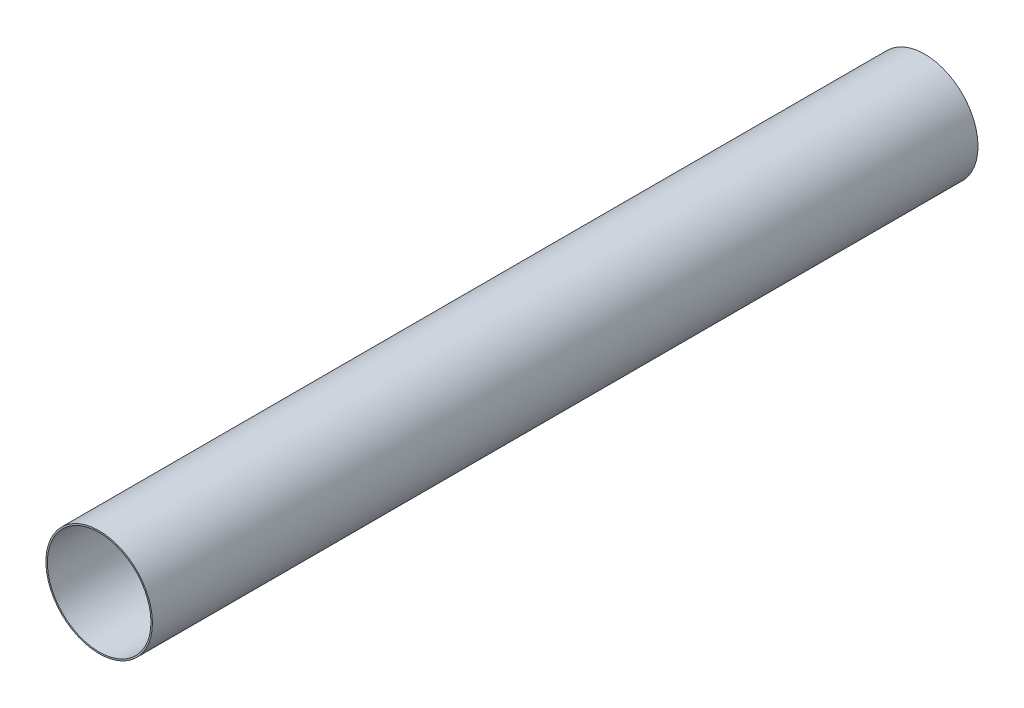
SolidWorks part; units mm, degrees
ref_plane "Plan de face" through (0, 0, 0) normal (0, 0, 1) x (1, 0, 0)
ref_plane "Plan de dessus" through (0, 0, 0) normal (0, 1, 0) x (1, 0, 0)
ref_plane "Plan de droite" through (0, 0, 0) normal (1, 0, 0) x (0, 0, -1)
sketch "Esquisse1" plane through (0, 0, 0) normal (0, 0, 1) x (1, 0, 0)
  circle A0 centre (0, 0) radius 50.8
  circle A1 centre (0, 0) radius 49.403
  dimension "D1" = 101.6
  dimension "D2" = 98.806
extrude "Boss.-Extru.1" add sketch "Esquisse1" along normal blind 787.4
